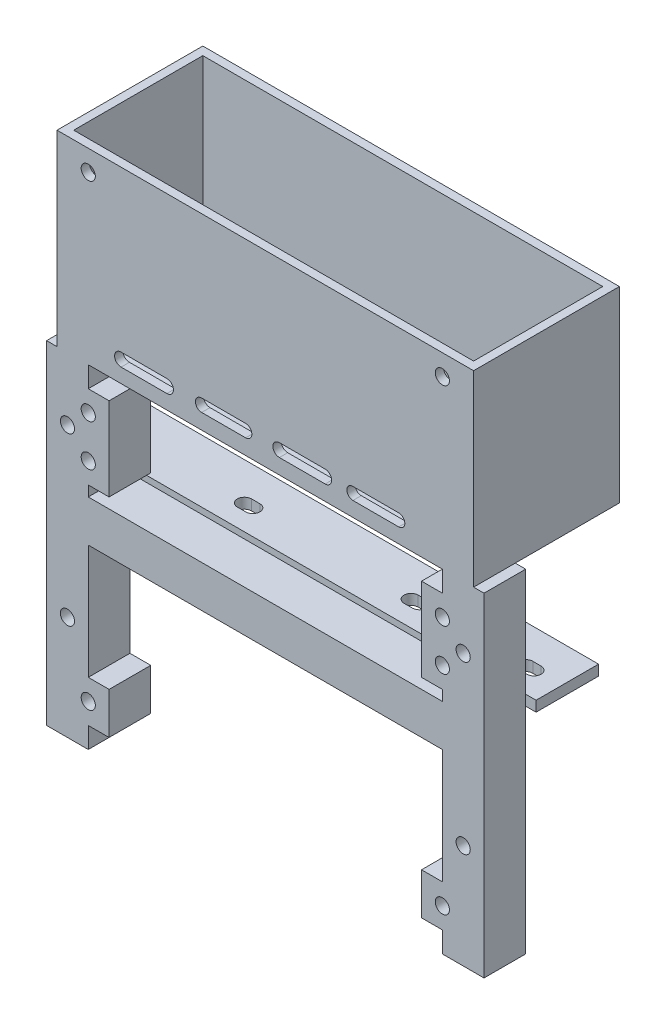
SolidWorks part; units mm, degrees
ref_plane "前视基准面" through (0, 0, 0) normal (0, 0, 1) x (1, 0, 0)
ref_plane "上视基准面" through (0, 0, 0) normal (0, 1, 0) x (1, 0, 0)
ref_plane "右视基准面" through (0, 0, 0) normal (1, 0, 0) x (0, 0, -1)
other "Configuration Table"
sketch "V3 box footprint 100 x 45 mm" plane through (0, 0, 0) normal (0, 0, 1) x (1, 0, 0)
  line L1 (-50, 0) -> (50, 0)
  line L2 (-50, 0) -> (-50, 45)
  line L3 (-50, 45) -> (50, 45)
  line L4 (50, 0) -> (50, 45)
extrude "V3 box height 35 mm" add sketch "V3 box footprint 100 x 45 mm" along normal blind 35
sketch "V3 rear opening 96 x 31 mm" plane through (0, 45, 0) normal (0, 1, 0) x (1, 0, 0)
  line L1 (-48, -2) -> (48, -2)
  line L2 (-48, -2) -> (-48, -33)
  line L3 (-48, -33) -> (48, -33)
  line L4 (48, -2) -> (48, -33)
extrude "V3 cavity all walls 2 mm" cut sketch "V3 rear opening 96 x 31 mm" against normal blind 43
sketch "V3 square beams 10 x 10 pitch 95 mm" plane through (0, 0, 0) normal (0, -1, 0) x (1, 0, 0)
  line L1 (-52.5, 25) -> (-42.5, 25)
  line L2 (-52.5, 25) -> (-52.5, 35)
  line L3 (-52.5, 35) -> (-42.5, 35)
  line L4 (-42.5, 25) -> (-42.5, 35)
  line L6 (42.5, 25) -> (52.5, 25)
  line L7 (42.5, 25) -> (42.5, 35)
  line L8 (42.5, 35) -> (52.5, 35)
  line L9 (52.5, 25) -> (52.5, 35)
extrude "V3 forward beam length 65 mm" add sketch "V3 square beams 10 x 10 pitch 95 mm" along normal blind 65
sketch "V3 left PCB ear profile" plane through (-42.5, 0, 0) normal (1, 0, 0) x (0, 0, -1)
  line L1 (-25, -25) -> (-35, -25)
  line L2 (-25, -25) -> (-25, -15)
  line L3 (-25, -15) -> (-35, -15)
  line L4 (-35, -25) -> (-35, -15)
extrude "V3 left inward ear 5 mm" add sketch "V3 left PCB ear profile" along normal blind 5
sketch "V3 right PCB ear profile" plane through (42.5, 0, 0) normal (-1, 0, 0) x (0, 0, 1)
  line L1 (25, -25) -> (35, -25)
  line L2 (25, -25) -> (25, -15)
  line L3 (25, -15) -> (35, -15)
  line L4 (35, -25) -> (35, -15)
extrude "V3 right inward ear 5 mm" add sketch "V3 right PCB ear profile" along normal blind 5
sketch "V3 PCB roof pair pitch 85 mm" plane through (0, 0, 35) normal (0, 0, 1) x (1, 0, 0)
  circle A0 centre (-42.5, 40) radius 1.7
  circle A1 centre (42.5, 40) radius 1.7
extrude "V3 M3 roof holes diameter 3.4 mm" cut sketch "V3 PCB roof pair pitch 85 mm" against normal blind 2
sketch "V3 PCB forward pair row spacing 60 mm" plane through (0, 0, 35) normal (0, 0, 1) x (1, 0, 0)
  circle A0 centre (-42.5, -20) radius 1.7
  circle A1 centre (42.5, -20) radius 1.7
extrude "V3 M3 PCB ear holes" cut sketch "V3 PCB forward pair row spacing 60 mm" against normal blind 10
sketch "V3 chassis top holes width 95 depth 40 mm" plane through (0, 0, 35) normal (0, 0, 1) x (1, 0, 0)
  circle A0 centre (-47.5, -55) radius 1.7
  circle A1 centre (-47.5, -15) radius 1.7
  circle A2 centre (47.5, -55) radius 1.7
  circle A3 centre (47.5, -15) radius 1.7
extrude "V3 M3 beam top bottom holes" cut sketch "V3 chassis top holes width 95 depth 40 mm" against normal blind 10
sketch "V3 hanging plate offset 26 thickness 2.5 mm" plane through (0, 0, 25) normal (0, 0, -1) x (-1, 0, 0)
  line L1 (55, -28.5) -> (-55, -28.5)
  line L2 (55, -28.5) -> (55, -26)
  line L3 (55, -26) -> (-55, -26)
  line L4 (-55, -28.5) -> (-55, -26)
extrude "V3 mounting plate downward 15 mm width 110" add sketch "V3 hanging plate offset 26 thickness 2.5 mm" along normal blind 15
sketch "V3 slots 6 mm below beam underside centers 20 and 47.5" plane through (0, -28.5, 0) normal (0, -1, 0) x (1, 0, 0)
  line L0 (-48.5, 19) -> (-46.5, 19) construction
  line L1 (-48.5, 20.7) -> (-46.5, 20.7)
  line L2 (-48.5, 17.3) -> (-46.5, 17.3)
  line L3 (-21, 19) -> (-19, 19) construction
  line L4 (-21, 20.7) -> (-19, 20.7)
  line L5 (-21, 17.3) -> (-19, 17.3)
  line L6 (19, 19) -> (21, 19) construction
  line L7 (19, 20.7) -> (21, 20.7)
  line L8 (19, 17.3) -> (21, 17.3)
  line L9 (46.5, 19) -> (48.5, 19) construction
  line L10 (46.5, 20.7) -> (48.5, 20.7)
  line L11 (46.5, 17.3) -> (48.5, 17.3)
  arc A0 (-48.5, 20.7) -> (-48.5, 17.3) centre (-48.5, 19) ccw
  arc A1 (-46.5, 17.3) -> (-46.5, 20.7) centre (-46.5, 19) ccw
  arc A2 (-21, 20.7) -> (-21, 17.3) centre (-21, 19) ccw
  arc A3 (-19, 17.3) -> (-19, 20.7) centre (-19, 19) ccw
  arc A4 (19, 20.7) -> (19, 17.3) centre (19, 19) ccw
  arc A5 (21, 17.3) -> (21, 20.7) centre (21, 19) ccw
  arc A6 (46.5, 20.7) -> (46.5, 17.3) centre (46.5, 19) ccw
  arc A7 (48.5, 17.3) -> (48.5, 20.7) centre (48.5, 19) ccw
  point P2 (-47.5, 19)
  point P7 (-20, 19)
  point P14 (20, 19)
  point P21 (47.5, 19)
  dimension "D1" = 3.4
  dimension "D2" = 2
  dimension "D3" = 3.4
  dimension "D4" = 2
  dimension "D5" = 3.4
  dimension "D6" = 2
  dimension "D7" = 3.4
  dimension "D8" = 2
extrude "Four horizontal slots 3.4 x 5.4 mm" cut sketch "V3 slots 6 mm below beam underside centers 20 and 47.5" against normal blind 2.5
sketch "草图1" plane through (0, 0, 35) normal (0, 0, 1) x (1, 0, 0)
  line L0 (-34.6201, 5) -> (-23.6201, 5) construction
  line L1 (-34.6201, 6.488) -> (-23.6201, 6.488)
  line L2 (-34.6201, 3.512) -> (-23.6201, 3.512)
  line L3 (21.03, 5) -> (32.03, 5) construction
  line L6 (21.03, 6.488) -> (32.03, 6.488)
  line L7 (21.03, 3.512) -> (32.03, 3.512)
  arc A0 (-34.6201, 6.488) -> (-34.6201, 3.512) centre (-34.6201, 5) ccw
  arc A1 (-23.6201, 3.512) -> (-23.6201, 6.488) centre (-23.6201, 5) ccw
  arc A4 (21.03, 6.488) -> (21.03, 3.512) centre (21.03, 5) ccw
  arc A5 (32.03, 3.512) -> (32.03, 6.488) centre (32.03, 5) ccw
  point P2 (-29.1201, 5)
  point P9 (26.53, 5)
sketch "草图2" plane through (0, 0, 0) normal (0, 0, -1) x (-1, 0, 0)
  line L0 (-32.03, 5) -> (-21.03, 5) construction
  line L1 (-32.03, 6.4595) -> (-21.03, 6.4595)
  line L2 (-32.03, 3.5405) -> (-21.03, 3.5405)
  line L3 (23.6201, 5) -> (34.6201, 5) construction
  line L4 (23.6201, 6.5587) -> (34.6201, 6.5587)
  line L5 (23.6201, 3.4413) -> (34.6201, 3.4413)
  arc A0 (-32.03, 6.4595) -> (-32.03, 3.5405) centre (-32.03, 5) ccw
  arc A1 (-21.03, 3.5405) -> (-21.03, 6.4595) centre (-21.03, 5) ccw
  arc A2 (23.6201, 6.5587) -> (23.6201, 3.4413) centre (23.6201, 5) ccw
  arc A3 (34.6201, 3.4413) -> (34.6201, 6.5587) centre (34.6201, 5) ccw
  point P4 (-26.53, 5)
  point P9 (29.1201, 5)
extrude "切除-拉伸1" cut sketch "草图2" against normal through all
sketch "H crossmember 10 x 10 mm at beam midpoint" plane through (-42.5, 0, 0) normal (1, 0, 0) x (0, 0, -1)
  line L1 (-25, -37.5) -> (-35, -37.5)
  line L2 (-25, -37.5) -> (-25, -27.5)
  line L3 (-25, -27.5) -> (-35, -27.5)
  line L4 (-35, -37.5) -> (-35, -27.5)
extrude "H crossmember 85 mm" add sketch "H crossmember 10 x 10 mm at beam midpoint" along normal blind 85
sketch "Beam cavities 6 mm wide preserving screw collars" plane through (0, 0, 35) normal (0, 0, 1) x (1, 0, 0)
  line L1 (-50.5, -65) -> (-44.5, -65)
  line L2 (-50.5, -65) -> (-50.5, -59)
  line L3 (-50.5, -59) -> (-44.5, -59)
  line L4 (-44.5, -65) -> (-44.5, -59)
  line L6 (-50.5, -51) -> (-44.5, -51)
  line L7 (-50.5, -51) -> (-50.5, -24)
  line L8 (-50.5, -24) -> (-44.5, -24)
  line L9 (-44.5, -51) -> (-44.5, -24)
  line L11 (-50.5, -11) -> (-44.5, -11)
  line L12 (-50.5, -11) -> (-50.5, -2)
  line L13 (-50.5, -2) -> (-44.5, -2)
  line L14 (-44.5, -11) -> (-44.5, -2)
  line L16 (44.5, -65) -> (50.5, -65)
  line L17 (44.5, -65) -> (44.5, -59)
  line L18 (44.5, -59) -> (50.5, -59)
  line L19 (50.5, -65) -> (50.5, -59)
  line L21 (44.5, -51) -> (50.5, -51)
  line L22 (44.5, -51) -> (44.5, -24)
  line L23 (44.5, -24) -> (50.5, -24)
  line L24 (50.5, -51) -> (50.5, -24)
  line L26 (44.5, -11) -> (50.5, -11)
  line L27 (44.5, -11) -> (44.5, -2)
  line L28 (44.5, -2) -> (50.5, -2)
  line L29 (50.5, -11) -> (50.5, -2)
extrude "Longitudinal beam walls 2 mm - inner height 6 mm" cut sketch "Beam cavities 6 mm wide preserving screw collars" against normal blind 6 from offset 2
sketch "H crossmember cavity connects both beam cavities" plane through (0, 0, 35) normal (0, 0, 1) x (1, 0, 0)
  line L1 (-44.5, -35.5) -> (44.5, -35.5)
  line L2 (-44.5, -35.5) -> (-44.5, -29.5)
  line L3 (-44.5, -29.5) -> (44.5, -29.5)
  line L4 (44.5, -35.5) -> (44.5, -29.5)
extrude "H crossmember walls 2 mm" cut sketch "H crossmember cavity connects both beam cavities" against normal blind 6 from offset 2
sketch "草图7" plane through (0, 0, 35) normal (0, 0, 1) x (1, 0, 0)
  line L0 (-15.2765, 5.1864) -> (-4.7235, 5.1864) construction
  line L1 (-15.2765, 6.6864) -> (-4.7235, 6.6864)
  line L2 (-15.2765, 3.6864) -> (-4.7235, 3.6864)
  line L3 (3.3727, 5.1864) -> (14.3727, 5.1864) construction
  line L4 (3.3727, 6.6864) -> (14.3727, 6.6864)
  line L5 (3.3727, 3.6864) -> (14.3727, 3.6864)
  arc A0 (-15.2765, 6.6864) -> (-15.2765, 3.6864) centre (-15.2765, 5.1864) ccw
  arc A1 (-4.7235, 3.6864) -> (-4.7235, 6.6864) centre (-4.7235, 5.1864) ccw
  arc A2 (3.3727, 6.6864) -> (3.3727, 3.6864) centre (3.3727, 5.1864) ccw
  arc A3 (14.3727, 3.6864) -> (14.3727, 6.6864) centre (14.3727, 5.1864) ccw
  point P2 (-10, 5.1864)
  point P7 (8.8727, 5.1864)
sketch "草图8" plane through (0, 0, 0) normal (0, 0, -1) x (-1, 0, 0)
  line L0 (-14.3727, 5.1864) -> (-3.3727, 5.1864) construction
  line L1 (-14.3727, 6.733) -> (-3.3727, 6.733)
  line L2 (-14.3727, 3.6397) -> (-3.3727, 3.6397)
  line L3 (4.7235, 5.1864) -> (15.2765, 5.1864) construction
  line L4 (4.7235, 6.6864) -> (15.2765, 6.6864)
  line L5 (4.7235, 3.6864) -> (15.2765, 3.6864)
  arc A0 (-14.3727, 6.733) -> (-14.3727, 3.6397) centre (-14.3727, 5.1864) ccw
  arc A1 (-3.3727, 3.6397) -> (-3.3727, 6.733) centre (-3.3727, 5.1864) ccw
  arc A2 (4.7235, 6.6864) -> (4.7235, 3.6864) centre (4.7235, 5.1864) ccw
  arc A3 (15.2765, 3.6864) -> (15.2765, 6.6864) centre (15.2765, 5.1864) ccw
  point P4 (-8.8727, 5.1864)
  point P9 (10, 5.1864)
extrude "切除-拉伸4" cut sketch "草图8" against normal through all
sketch "V6 extend 10 x 10 hollow beams with 2 mm walls" plane through (0, -65, 0) normal (0, -1, 0) x (1, 0, 0)
  line L1 (-52.5, 25) -> (-42.5, 25)
  line L2 (-52.5, 25) -> (-52.5, 35)
  line L3 (-52.5, 35) -> (-42.5, 35)
  line L4 (-42.5, 25) -> (-42.5, 35)
  line L6 (-50.5, 27) -> (-44.5, 27)
  line L7 (-50.5, 27) -> (-50.5, 33)
  line L8 (-50.5, 33) -> (-44.5, 33)
  line L9 (-44.5, 27) -> (-44.5, 33)
  line L11 (42.5, 25) -> (52.5, 25)
  line L12 (42.5, 25) -> (42.5, 35)
  line L13 (42.5, 35) -> (52.5, 35)
  line L14 (52.5, 25) -> (52.5, 35)
  line L16 (44.5, 27) -> (50.5, 27)
  line L17 (44.5, 27) -> (44.5, 33)
  line L18 (44.5, 33) -> (50.5, 33)
  line L19 (50.5, 27) -> (50.5, 33)
extrude "V6 hollow beam extensions 15 mm" add sketch "V6 extend 10 x 10 hollow beams with 2 mm walls" along normal blind 15
sketch "V6 four full-depth PCB pads centers x42.5 y-70 and -10" plane through (0, 0, 35) normal (0, 0, 1) x (1, 0, 0)
  line L1 (-52.5, -75) -> (-37.5, -75)
  line L2 (-52.5, -75) -> (-52.5, -65)
  line L3 (-52.5, -65) -> (-37.5, -65)
  line L4 (-37.5, -75) -> (-37.5, -65)
  line L6 (37.5, -75) -> (52.5, -75)
  line L7 (37.5, -75) -> (37.5, -65)
  line L8 (37.5, -65) -> (52.5, -65)
  line L9 (52.5, -75) -> (52.5, -65)
  line L11 (-52.5, -15) -> (-37.5, -15)
  line L12 (-52.5, -15) -> (-52.5, -5)
  line L13 (-52.5, -5) -> (-37.5, -5)
  line L14 (-37.5, -15) -> (-37.5, -5)
  line L16 (37.5, -15) -> (52.5, -15)
  line L17 (37.5, -15) -> (37.5, -5)
  line L18 (37.5, -5) -> (52.5, -5)
  line L19 (52.5, -15) -> (52.5, -5)
extrude "V6 solid screw pads with 5 mm inward ears" add sketch "V6 four full-depth PCB pads centers x42.5 y-70 and -10" against normal blind 10
sketch "V6 PCB holes 85 x 60 mm and retained chassis holes" plane through (0, 0, 35) normal (0, 0, 1) x (1, 0, 0)
  circle A0 centre (-42.5, -70) radius 1.7
  circle A1 centre (-42.5, -10) radius 1.7
  circle A2 centre (42.5, -70) radius 1.7
  circle A3 centre (42.5, -10) radius 1.7
  circle A4 centre (-47.5, -15) radius 1.7
  circle A5 centre (47.5, -15) radius 1.7
extrude "V6 four PCB M3 holes through reinforced beam pads" cut sketch "V6 PCB holes 85 x 60 mm and retained chassis holes" against normal blind 10
